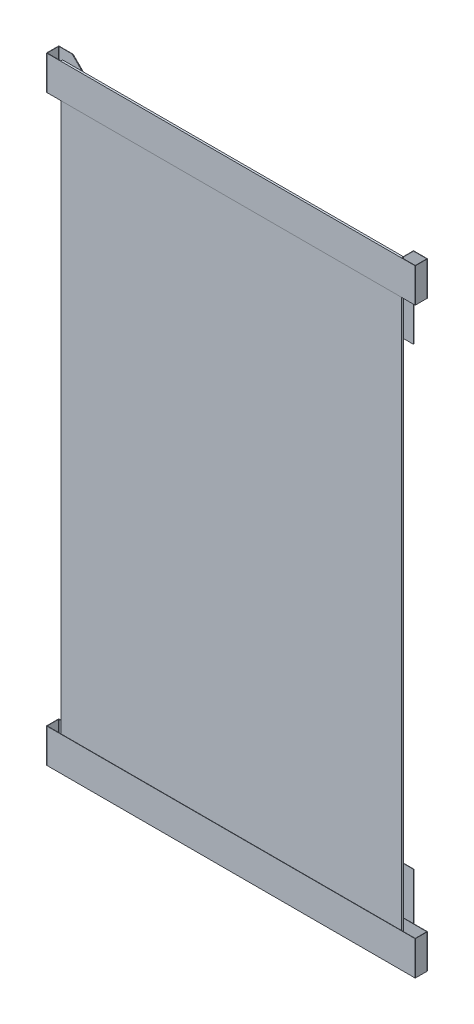
SolidWorks part; units mm, degrees
ref_plane "Front Plane" through (0, 0, 0) normal (0, 0, 1) x (1, 0, 0)
ref_plane "Top Plane" through (0, 0, 0) normal (0, 1, 0) x (1, 0, 0)
ref_plane "Right Plane" through (0, 0, 0) normal (1, 0, 0) x (0, 0, -1)
ref_plane "Plane1" through (0, 0, 0.25) normal (0, 0, 1) x (1, 0, 0)
sketch "Sketch1" plane through (0, 0, 0.25) normal (0, 0, 1) x (1, 0, 0)
  line L0 (25, -42.75) -> (25, 45.25)
  line L1 (25, 45.25) -> (-25, 45.25)
  line L2 (-25, 45.25) -> (-25, -42.75)
  line L3 (-25, -42.75) -> (25, -42.75)
  dimension "D1" = 50
  dimension "D2" = 88
  dimension "D3" = 25
  dimension "D4" = 42.75
extrude "Boss-Extrude1" add sketch "Sketch1" against normal blind 0.25
ref_plane "Plane3" through (0, -45.25, 0) normal (0, -1, 0) x (-1, 0, 0)
sketch "Sketch4" plane through (0, -45.25, 0) normal (0, -1, 0) x (-1, 0, 0)
  line L1 (-26.95, -0.25) -> (26.95, -0.25)
  line L3 (-27, -0.3) -> (27, -0.3)
  line L5 (0, 0) -> (0, 2.5169) construction
  line L6 (25, -0.25) -> (-25, -0.25) construction
  line L7 (-20, 1.5) -> (-20, 1.45)
  line L8 (27, -0.2) -> (27, 1.4)
  line L9 (-26.95, 1.45) -> (-20, 1.45)
  line L10 (27.05, -0.25) -> (27.05, 1.45)
  line L11 (27, 1.5) -> (20, 1.5)
  line L12 (-27, 1.5) -> (-20, 1.5)
  line L13 (26.95, 1.45) -> (20, 1.45)
  line L14 (20, 1.5) -> (20, 1.45)
  line L15 (-27.05, -0.25) -> (-27.05, 1.45)
  line L16 (-27, -0.2) -> (-27, 1.4)
  arc A0 (27, 1.5) -> (27.05, 1.45) centre (27, 1.45) cw
  arc A1 (27, 1.4) -> (26.95, 1.45) centre (26.95, 1.4) ccw
  arc A2 (27, -0.3) -> (27.05, -0.25) centre (27, -0.25) ccw
  arc A3 (26.95, -0.25) -> (27, -0.2) centre (26.95, -0.2) ccw
  arc A4 (-26.95, -0.25) -> (-27, -0.2) centre (-26.95, -0.2) cw
  arc A5 (-27, -0.3) -> (-27.05, -0.25) centre (-27, -0.25) cw
  arc A6 (-27, 1.4) -> (-26.95, 1.45) centre (-26.95, 1.4) cw
  arc A7 (-27, 1.5) -> (-27.05, 1.45) centre (-27, 1.45) ccw
  dimension "D1" = 0.05
  dimension "D2" = 7
  dimension "D3" = 54
  dimension "D4" = 0.05
  dimension "D5" = 0.05
  dimension "D6" = 1.7
extrude "Boss-Extrude2" add sketch "Sketch4" against normal blind 5
sketch "Sketch5" plane through (0, 0, -1.5) normal (0, 0, -1) x (-1, 0, 0)
  line L0 (0, 0) -> (0, -53.2903) construction
  line L1 (20, -45.25) -> (25, -45.25)
  line L2 (20, -45.25) -> (20, -33.35)
  line L3 (20, -33.35) -> (25, -33.35)
  line L4 (25, -45.25) -> (25, -33.35)
  line L5 (-25, -45.25) -> (-25, -33.35)
  line L6 (-20, -33.35) -> (-25, -33.35)
  line L7 (-20, -45.25) -> (-20, -33.35)
  line L8 (-20, -45.25) -> (-25, -45.25)
  dimension "D1" = 5
  dimension "D2" = 11.9
extrude "Boss-Extrude3" add sketch "Sketch5" along normal blind 0.05
sketch "Sketch6" plane through (0, 0, -1.55) normal (0, 0, -1) x (-1, 0, 0)
  line L1 (20, -45.25) -> (25, -45.25)
  line L2 (20, -45.25) -> (20, -40.2549)
  line L3 (0, 0) -> (0, -53.2763) construction
  line L4 (-20, -40.2549) -> (-25, -45.25)
  line L5 (20, -40.2549) -> (25, -45.25)
  line L6 (-20, -45.25) -> (-20, -40.2549)
  line L7 (-20, -45.25) -> (-25, -45.25)
  dimension "D1" = 4.9951
  dimension "D2" = 5
extrude "Cut-Extrude1" cut sketch "Sketch6" against normal blind 0.2
fillet "Fillet1" radius 0.04 4 edges at (-22.5, -42.7525, -1.45) (-22.5, -42.7525, -1.55) (22.5, -42.7525, -1.55) (22.5, -42.7525, -1.45)
sketch "Sketch7" plane through (0, 0, 0.25) normal (0, 0, 1) x (1, 0, 0)
  line L0 (-25, 0) -> (25, 0) construction
  line L1 (-25, 45.25) -> (-25, -40.25) construction
  line L2 (25, -40.25) -> (25, 45.25) construction
  dimension "D1" = 0
ref_plane "Plane4" through (0, 0, 0) normal (0, -1, 0) x (-1, 0, 0)
mirror "Mirror1" about plane through (0, 0, 0) normal (0, -1, 0) of "Boss-Extrude2", "Boss-Extrude3", "Cut-Extrude1", "Fillet1"
